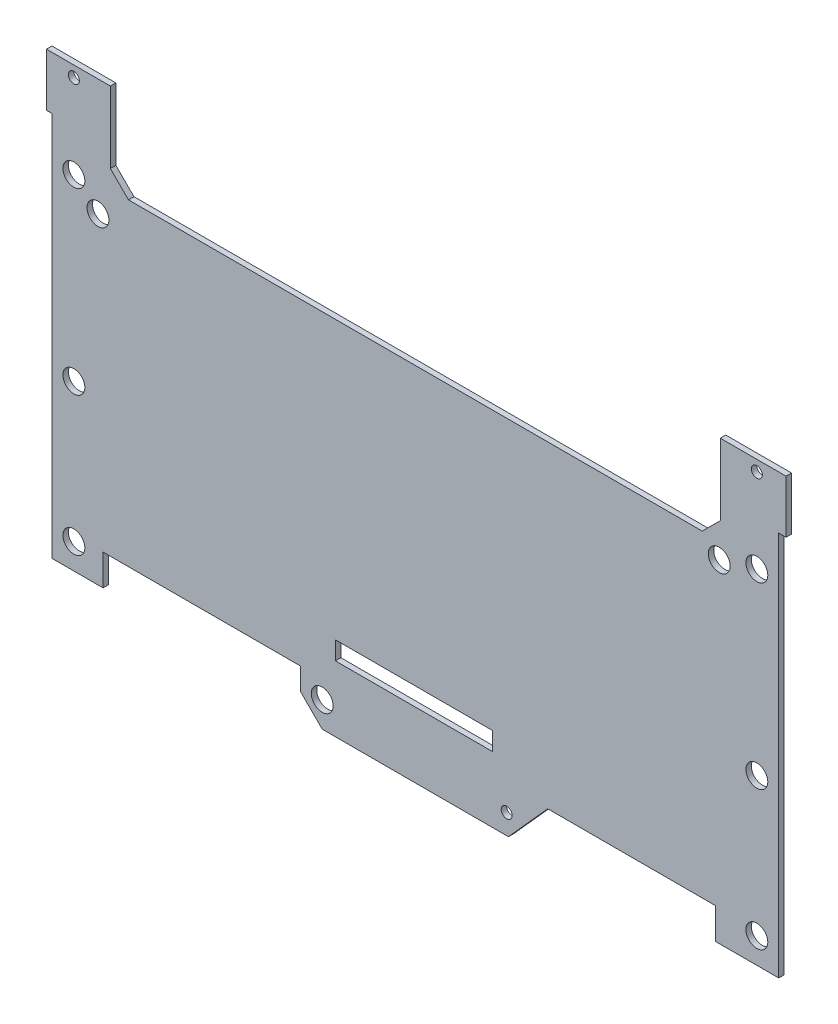
SolidWorks part; units mm, degrees
ref_plane "Front Plane" through (0, 0, 0) normal (0, 0, 1) x (1, 0, 0)
ref_plane "Top Plane" through (0, 0, 0) normal (0, 1, 0) x (1, 0, 0)
ref_plane "Right Plane" through (0, 0, 0) normal (1, 0, 0) x (0, 0, -1)
sketch "Sketch1" plane through (0, 0, 0) normal (0, 0, 1) x (1, 0, 0)
  line L0 (-100.6, 103) -> (-83.1, 103)
  line L1 (-83.1, 103) -> (-83.1, 83.4497)
  line L2 (-83.1, 83.4497) -> (-78.1503, 78.5)
  line L3 (-78.1503, 78.5) -> (78.9503, 78.5)
  line L4 (78.9503, 78.5) -> (83.9, 83.4497)
  line L5 (83.9, 83.4497) -> (83.9, 103)
  line L6 (83.9, 103) -> (101.9, 103)
  line L7 (101.9, 103) -> (101.9, 88.5)
  line L8 (101.9, 88.5) -> (99.9, 88.5)
  line L9 (99.9, 88.5) -> (99.9, -17)
  line L10 (99.9, -17) -> (82.65, -17)
  line L11 (82.65, -17) -> (82.65, -8.5)
  line L12 (82.65, -8.5) -> (36.65, -8.5)
  line L13 (36.65, -8.5) -> (25.9, -20.5)
  line L14 (25.9, -20.5) -> (-25.1, -20.5)
  line L15 (-25.1, -20.5) -> (-31.1, -14.5)
  line L16 (-31.1, -14.5) -> (-31.1, -8.5)
  line L17 (-31.1, -8.5) -> (-85.1, -8.5)
  line L18 (-85.1, -8.5) -> (-85.1, -17)
  line L19 (-85.1, -17) -> (-99.1, -17)
  line L20 (-99.1, -17) -> (-99.1, 88.5)
  line L21 (-99.1, 88.5) -> (-100.6, 88.5)
  line L22 (-100.6, 88.5) -> (-100.6, 103)
  line L23 (-31.1, -8.5) -> (36.65, -8.5) construction
  line L24 (-83.1, 103) -> (83.9, 103) construction
  line L25 (-93.1, 77) -> (93.9, 77) construction
  line L26 (-21.5, 2.5) -> (21.5, 2.5)
  line L27 (-21.5, 2.5) -> (-21.5, -2.5)
  line L28 (-21.5, -2.5) -> (21.5, -2.5)
  line L29 (21.5, 2.5) -> (21.5, -2.5)
  line L30 (-21.5, 2.5) -> (21.5, -2.5) construction
  line L31 (-21.5, -2.5) -> (21.5, 2.5) construction
  line L32 (-93.1, 28) -> (93.9, 28) construction
  line L33 (93.9, -10) -> (-93.1, -10) construction
  circle A0 centre (93.9, 77) radius 3
  circle A1 centre (83.6, 74) radius 3
  circle A2 centre (93.9, -10) radius 3
  circle A3 centre (93.9, 28) radius 3
  circle A4 centre (93.9, 100) radius 1.5
  circle A5 centre (25.4, -15) radius 1.5
  circle A6 centre (-25.1, -13.5) radius 3
  circle A7 centre (-93.1, -10) radius 3
  circle A8 centre (-93.1, 28) radius 3
  circle A9 centre (-93.1, 77) radius 3
  circle A10 centre (-86.5, 71) radius 3
  circle A11 centre (-93.1, 100) radius 1.5
  point P47 (0, 0)
  point P52 (-22.7266, -26.5)
  point P53 (22.5888, -25.0531)
  dimension "D23" = 3
  dimension "D24" = 6
  dimension "D25" = 6
  dimension "D26" = 6
  dimension "D27" = 6
  dimension "D28" = 6
  dimension "D29" = 3
  dimension "D30" = 6
  dimension "D31" = 6
  dimension "D32" = 6
  dimension "D33" = 6
  dimension "D34" = 3
  dimension "D42" = 6
  dimension "D43" = 6
  dimension "D44" = 6
  dimension "D45" = 7
  dimension "D46" = 38
  dimension "D1" = 199
  dimension "D2" = 87
  dimension "D3" = 14.5
  dimension "D4" = 14.5
  dimension "D5" = 16
  dimension "D6" = 16
  dimension "D7" = 1.5
  dimension "D8" = 18
  dimension "D9" = 120
  dimension "D10" = 8.5
  dimension "D11" = 7
  dimension "D12" = 45
  dimension "D13" = 7
  dimension "D14" = 45
  dimension "D15" = 17.25
  dimension "D16" = 46
  dimension "D17" = 14
  dimension "D18" = 54
  dimension "D19" = 45
  dimension "D20" = 12
  dimension "D21" = 6
  dimension "D22" = 51
  dimension "D35" = 43
  dimension "D36" = 5
  dimension "D37" = 18
  dimension "D38" = 78.4
  dimension "D39" = 6
  dimension "D40" = 6
  dimension "D41" = 6
  dimension "D47" = 49
  dimension "D48" = 8.5
  dimension "D49" = 7
  dimension "D50" = 6
  dimension "D51" = 5.5
  dimension "D52" = 0.5
  dimension "D53" = 16.3
  dimension "D54" = 12.6
  dimension "D55" = 32
  dimension "D56" = 29
  dimension "D57" = 10
  dimension "D58" = 3
  dimension "D59" = 3
  dimension "D60" = 10
extrude "Boss-Extrude1" add sketch "Sketch1" along normal blind 1.5
